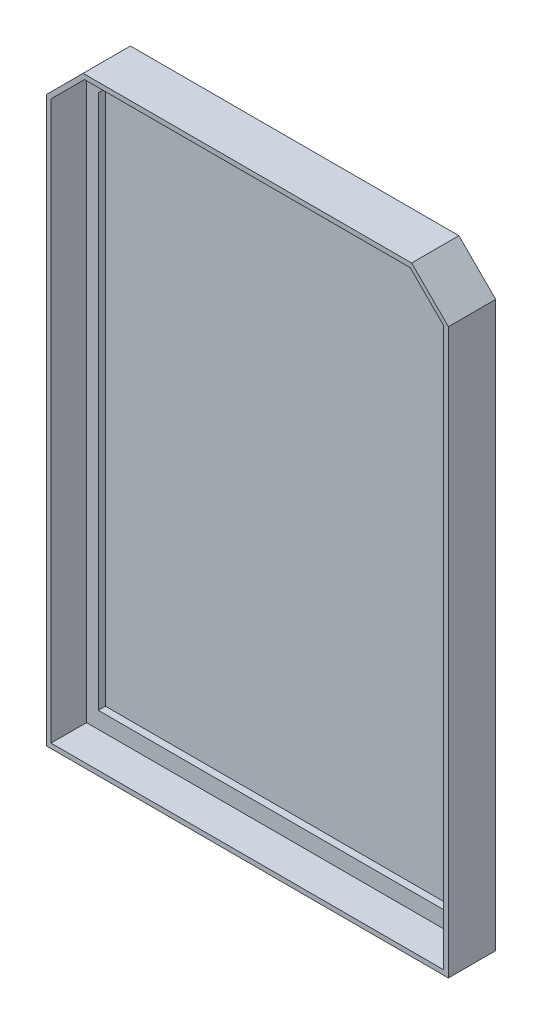
SolidWorks part; units mm, degrees
ref_plane "Front Plane" through (0, 0, 0) normal (1, 0, 0) x (0, 1, 0)
ref_plane "Top Plane" through (0, 0, 0) normal (0, 0, 1) x (0, 1, 0)
ref_plane "Right Plane" through (0, 0, 0) normal (0, 1, 0) x (-1, 0, 0)
sketch "Sketch1" plane through (0, 0, 0) normal (0, 0, 1) x (0, 1, 0)
  line L0 (54.0503, 39) -> (59, 34.0503)
  line L1 (-62.5, -41.5) -> (62.5, -41.5) construction
  line L2 (-62.5, -41.5) -> (-62.5, 41.5)
  line L3 (-62.5, 41.5) -> (62.5, 41.5) construction
  line L4 (62.5, -41.5) -> (62.5, 41.5) construction
  line L5 (-62.5, -41.5) -> (62.5, 41.5) construction
  line L6 (-62.5, 41.5) -> (62.5, -41.5) construction
  line L7 (-59, -39) -> (59, -39) construction
  line L8 (-59, -39) -> (-59, 39)
  line L9 (-59, 39) -> (59, 39) construction
  line L10 (59, -39) -> (59, 39) construction
  line L11 (-59, -39) -> (59, 39) construction
  line L12 (-59, 39) -> (59, -39) construction
  line L13 (-63.5, -42.5) -> (63.5, -42.5) construction
  line L14 (-63.5, -42.5) -> (-63.5, 42.5)
  line L15 (-63.5, 42.5) -> (63.5, 42.5) construction
  line L16 (63.5, -42.5) -> (63.5, 42.5) construction
  line L17 (-63.5, -42.5) -> (63.5, 42.5) construction
  line L18 (-63.5, 42.5) -> (63.5, -42.5) construction
  line L19 (-59, 39) -> (54.0503, 39)
  line L20 (59, 34.0503) -> (59, -39) construction
  line L21 (59, -34.0503) -> (54.0503, -39)
  line L22 (59, -34.0503) -> (59, 34.0503)
  line L23 (54.0503, -39) -> (-59, -39)
  line L24 (55.4289, 41.5) -> (62.5, 34.4289)
  line L25 (62.5, -34.4289) -> (55.4289, -41.5)
  line L26 (55.4289, -41.5) -> (-62.5, -41.5)
  line L27 (62.5, -34.4289) -> (62.5, 34.4289)
  line L28 (55.4289, 41.5) -> (-62.5, 41.5)
  line L29 (55.7218, 42.5) -> (63.5, 34.7218)
  line L30 (63.5, -34.7218) -> (55.7218, -42.5)
  line L31 (55.7218, -42.5) -> (-63.5, -42.5)
  line L32 (63.5, -34.7218) -> (63.5, 34.7218)
  line L33 (55.7218, 42.5) -> (-63.5, 42.5)
  point P0 (0, 0)
  point P5 (0, 0)
  point P11 (0, 0)
  dimension "D1" = 83
  dimension "D2" = 125
  dimension "D3" = 118
  dimension "D4" = 78
  dimension "D5" = 85
  dimension "D6" = 127
  dimension "D7" = 7
  dimension "D8" = 45
  dimension "D9" = 7
  dimension "D10" = 45
  dimension "D11" = 10
  dimension "D12" = 10
  dimension "D13" = 11
  dimension "D14" = 11
extrude "Boss-Extrude1" add sketch "Sketch1" along normal blind 1.5 contours L1 L4 L3 L2 L10 L7 L8 L9
sketch "Sketch2" plane through (0, 0, 0) normal (0, 0, 1) x (0, 1, 0)
  line L4 (55.7218, 42.5) -> (-63.5, 42.5)
  line L5 (55.7218, 42.5) -> (-63.5, 42.5)
  line L6 (63.5, 34.7218) -> (55.7218, 42.5)
  line L7 (-63.5, 42.5) -> (-63.5, -42.5)
  line L11 (-63.5, 42.5) -> (-63.5, -42.5)
  line L12 (54.0503, 39) -> (-59, 39)
  line L13 (54.0503, 39) -> (-59, 39)
  line L14 (59, 34.0503) -> (54.0503, 39)
  line L15 (-59, 39) -> (-59, -39)
  line L19 (-59, 39) -> (-59, -39) construction
  line L20 (55.4289, 41.5) -> (-62.5, 41.5)
  line L21 (55.4289, 41.5) -> (-62.5, 41.5)
  line L22 (62.5, 34.4289) -> (55.4289, 41.5)
  line L23 (-62.5, 41.5) -> (-62.5, -41.5)
  line L27 (-62.5, 41.5) -> (-62.5, -41.5)
  line L30 (59, 34.0503) -> (54.0503, 39)
  line L31 (59, -34.0503) -> (59, 34.0503)
  line L32 (59, -34.0503) -> (59, 34.0503)
  line L33 (54.0503, -39) -> (59, -34.0503)
  line L34 (54.0503, -39) -> (59, -34.0503)
  line L35 (-59, -39) -> (54.0503, -39)
  line L36 (-59, -39) -> (54.0503, -39)
  line L37 (62.5, 34.4289) -> (55.4289, 41.5)
  line L38 (62.5, -34.4289) -> (62.5, 34.4289)
  line L39 (62.5, -34.4289) -> (62.5, 34.4289)
  line L40 (55.4289, -41.5) -> (62.5, -34.4289)
  line L41 (55.4289, -41.5) -> (62.5, -34.4289)
  line L42 (-62.5, -41.5) -> (55.4289, -41.5)
  line L43 (-62.5, -41.5) -> (55.4289, -41.5)
  line L44 (63.5, 34.7218) -> (55.7218, 42.5)
  line L45 (63.5, -34.7218) -> (63.5, 34.7218)
  line L46 (63.5, -34.7218) -> (63.5, 34.7218)
  line L47 (55.7218, -42.5) -> (63.5, -34.7218)
  line L48 (55.7218, -42.5) -> (63.5, -34.7218)
  line L49 (-63.5, -42.5) -> (55.7218, -42.5)
  line L50 (-63.5, -42.5) -> (55.7218, -42.5)
  dimension "D1" = 0
  dimension "D2" = 0
  dimension "D3" = 0
extrude "Boss-Extrude2" add sketch "Sketch2" along normal blind 9 contours L11 L50 L48 L46 L44 L5 L43 L27 L21 L37 L39 L41
sketch "Sketch3" plane through (0, 0, 0) normal (0, 0, 1) x (0, 1, 0)
  line L4 (55.7218, 42.5) -> (-63.5, 42.5)
  line L5 (55.7218, 42.5) -> (-63.5, 42.5)
  line L6 (63.5, 34.7218) -> (55.7218, 42.5)
  line L7 (-63.5, 42.5) -> (-63.5, -42.5)
  line L11 (-63.5, 42.5) -> (-63.5, -42.5)
  line L12 (54.0503, 39) -> (-59, 39)
  line L13 (54.0503, 39) -> (-59, 39)
  line L14 (59, 34.0503) -> (54.0503, 39)
  line L15 (-59, 39) -> (-59, -39)
  line L19 (-59, 39) -> (-59, -39) construction
  line L20 (55.4289, 41.5) -> (-62.5, 41.5)
  line L21 (55.4289, 41.5) -> (-62.5, 41.5)
  line L22 (62.5, 34.4289) -> (55.4289, 41.5)
  line L23 (-62.5, 41.5) -> (-62.5, -41.5)
  line L27 (-62.5, 41.5) -> (-62.5, -41.5) construction
  line L30 (59, 34.0503) -> (54.0503, 39)
  line L31 (59, -34.0503) -> (59, 34.0503)
  line L32 (59, -34.0503) -> (59, 34.0503)
  line L33 (54.0503, -39) -> (59, -34.0503)
  line L34 (54.0503, -39) -> (59, -34.0503)
  line L35 (-59, -39) -> (54.0503, -39)
  line L36 (-59, -39) -> (54.0503, -39)
  line L37 (62.5, 34.4289) -> (55.4289, 41.5)
  line L38 (62.5, -34.4289) -> (62.5, 34.4289)
  line L39 (62.5, -34.4289) -> (62.5, 34.4289)
  line L40 (55.4289, -41.5) -> (62.5, -34.4289)
  line L41 (55.4289, -41.5) -> (62.5, -34.4289)
  line L42 (-62.5, -41.5) -> (55.4289, -41.5)
  line L43 (-62.5, -41.5) -> (55.4289, -41.5)
  line L44 (63.5, 34.7218) -> (55.7218, 42.5)
  line L45 (63.5, -34.7218) -> (63.5, 34.7218)
  line L46 (63.5, -34.7218) -> (63.5, 34.7218)
  line L47 (55.7218, -42.5) -> (63.5, -34.7218)
  line L48 (55.7218, -42.5) -> (63.5, -34.7218)
  line L49 (-63.5, -42.5) -> (55.7218, -42.5)
  line L50 (-63.5, -42.5) -> (55.7218, -42.5)
  dimension "D1" = 0
  dimension "D2" = 0
  dimension "D3" = 0
extrude "Boss-Extrude3" add sketch "Sketch3" against normal blind 1
sketch "Sketch4" plane through (0, 0, -1) normal (0, 0, -1) x (1, 0, 0)
  circle A0 centre (0, 0) radius 5
  circle A1 centre (0, 0) radius 4
  dimension "D1" = 8
  dimension "D2" = 10
extrude "Boss-Extrude4" add sketch "Sketch4" along normal blind 10
fillet "Fillet1" radius 5 1 edges at (5, 0, -1)
